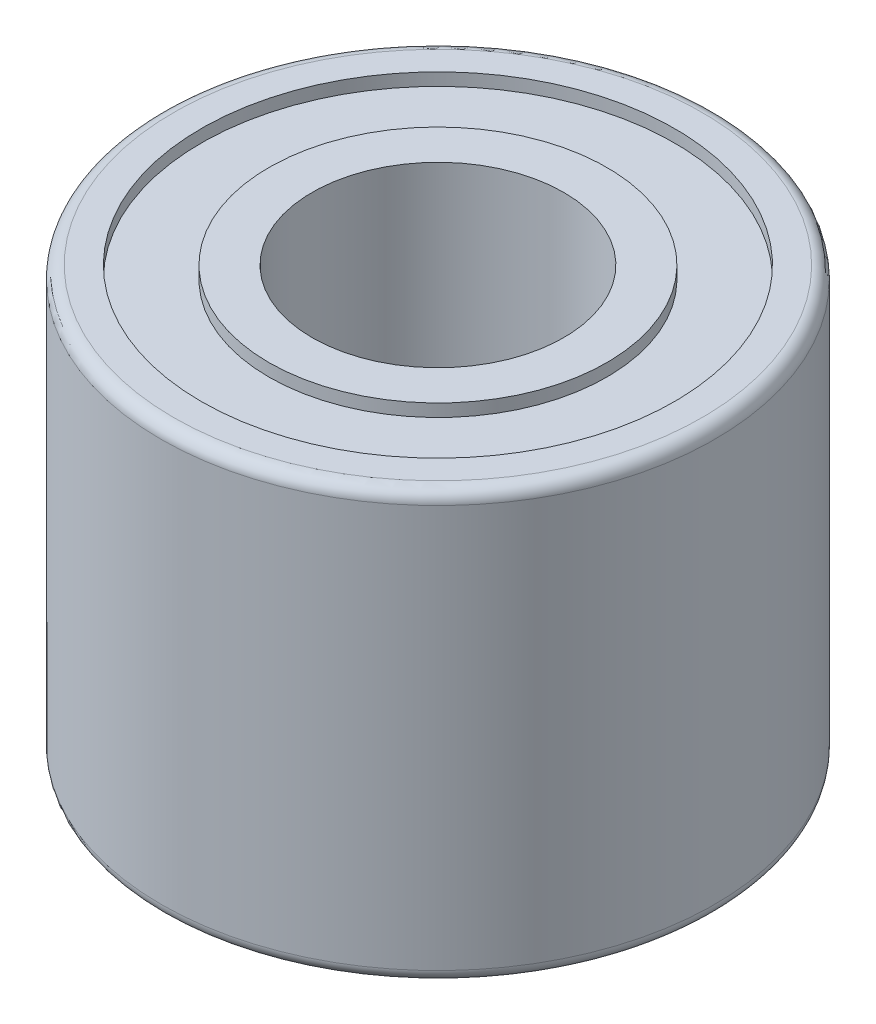
SolidWorks part; units mm, degrees
material "Malleable Cast Iron"
ref_plane "Front Plane" through (0, 0, 0) normal (0, 0, 1) x (1, 0, 0)
ref_plane "Top Plane" through (0, 0, 0) normal (0, 1, 0) x (1, 0, 0)
ref_plane "Right Plane" through (0, 0, 0) normal (1, 0, 0) x (0, 0, -1)
sketch "Sketch1" plane through (0, 0, 0) normal (0, 1, 0) x (1, 0, 0)
  circle A0 centre (0, 0) radius 5
  circle A1 centre (0, 0) radius 6.715
  dimension "D1" = 10
  dimension "D2" = 13.43
extrude "Boss-Extrude1" add sketch "Sketch1" along normal blind 17
ref_plane "Plane1" through (0, 8.5, 0) normal (0, 1, 0) x (1, 0, 0)
sketch "Sketch4" plane through (0, 8.5, 0) normal (0, 1, 0) x (1, 0, 0)
  circle A0 centre (0, 0) radius 9.4
  dimension "D1" = 18.8
extrude "Boss-Extrude2" add sketch "Sketch4" along normal mid plane 16
sketch "Sketch7" plane through (0, 17, 0) normal (0, 1, 0) x (1, 0, 0)
  circle A0 centre (0, 0) radius 11
  circle A1 centre (0, 0) radius 9.4
  dimension "D1" = 22
  dimension "D2" = 18.8
extrude "Boss-Extrude3" add sketch "Sketch7" against normal blind 17
sketch "Sketch8" plane through (0, 0.5, 0) normal (0, -1, 0) x (1, 0, 0)
  circle A0 centre (0, 0) radius 5
  dimension "D1" = 10
extrude "Cut-Extrude1" cut sketch "Sketch8" against normal blind 17
fillet "Fillet1" radius 0.5 2 edges at (0, 0, 11) (0, 17, 11)
